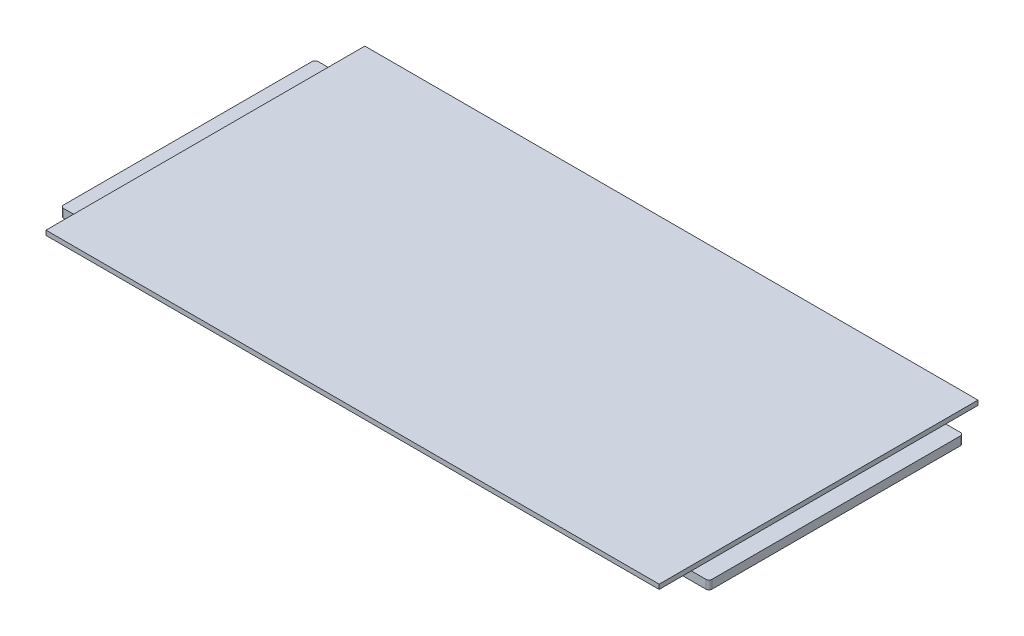
SolidWorks part; units mm, degrees
ref_plane "Front Plane" through (0, 0, 0) normal (0, 0, 1) x (1, 0, 0)
ref_plane "Top Plane" through (0, 0, 0) normal (0, 1, 0) x (1, 0, 0)
ref_plane "Right Plane" through (0, 0, 0) normal (1, 0, 0) x (0, 0, -1)
sketch "Sketch1" plane through (0, 0, 0) normal (0, 1, 0) x (1, 0, 0)
  line L1 (-671.5125, 263.525) -> (671.5125, 263.525)
  line L2 (-671.5125, 263.525) -> (-671.5125, -263.525)
  line L3 (-671.5125, -263.525) -> (671.5125, -263.525)
  line L4 (671.5125, 263.525) -> (671.5125, -263.525)
  line L5 (-671.5125, 263.525) -> (671.5125, -263.525) construction
  line L6 (-671.5125, -263.525) -> (671.5125, 263.525) construction
  point P0 (0, 0)
  dimension "D1" = 527.05
  dimension "D2" = 1343.025
extrude "Boss-Extrude1" add sketch "Sketch1" along normal blind 17.78
fillet "Fillet1" radius 6.35 4 edges at (-671.5125, 8.89, 263.525) (-671.5125, 8.89, -263.525) (671.5125, 8.89, -263.525) (671.5125, 8.89, 263.525)
hole_wizard "1/8 (0.125) Diameter Hole1" positions "Sketch3" profile "Sketch4" hole size "1/8" standard "ANSI Inch" end condition through all
sketch "Sketch3" plane through (0, 17.78, 0) normal (0, 1, 0) x (1, 0, 0)
  line L1 (-457.2, -152.4) -> (457.2, -152.4) construction
  line L2 (-457.2, -152.4) -> (-457.2, 152.4) construction
  line L3 (-457.2, 152.4) -> (457.2, 152.4) construction
  line L4 (457.2, -152.4) -> (457.2, 152.4) construction
  line L5 (-457.2, -152.4) -> (457.2, 152.4) construction
  line L6 (-457.2, 152.4) -> (457.2, -152.4) construction
  point P0 (0, 0)
  point P1 (457.2, 152.4)
  point P32 (-457.2, -152.4)
  point P33 (-457.2, 152.4)
  point P34 (457.2, -152.4)
  dimension "D1" = 914.4
  dimension "D2" = 304.8
sketch "Sketch4" plane through (0, 17.78, 0) normal (1, 0, 0) x (0, 0, 1)
  line L0 (0, 0) -> (0, 17.78)
  line L1 (0, 17.78) -> (1.5875, 17.78)
  line L2 (1.5875, 17.78) -> (1.5875, 0)
  line L5 (1.5875, 0) -> (0, 0)
  line L11 (0, -6.35) -> (0, 107.95) construction
  dimension "Thru Hole Dia." = 3.175
  dimension "Thru Hole Depth" = 17.78
sketch "Sketch2" plane through (0, 17.78, 0) normal (0, 1, 0) x (1, 0, 0)
  line L1 (-635, -330.2) -> (635, -330.2)
  line L2 (-635, -330.2) -> (-635, 330.2)
  line L3 (-635, 330.2) -> (635, 330.2)
  line L4 (635, -330.2) -> (635, 330.2)
  line L5 (-635, -330.2) -> (635, 330.2) construction
  line L6 (-635, 330.2) -> (635, -330.2) construction
  point P0 (0, 0)
  dimension "D1" = 660.4
  dimension "D2" = 1270
extrude "Boss-Extrude2" add sketch "Sketch2" along normal blind 9.525
